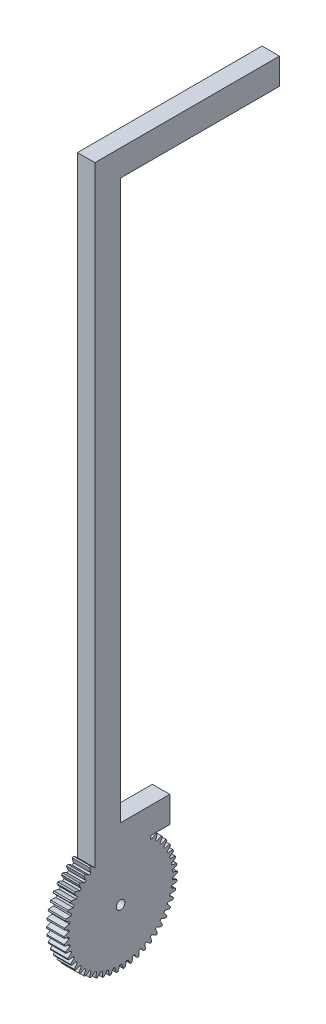
SolidWorks part; units mm, degrees
ref_plane "Plane1" through (0, 0, 0) normal (0, 0, 1) x (1, 0, 0)
ref_plane "Plane2" through (0, 0, 0) normal (0, 1, 0) x (1, 0, 0)
ref_plane "Plane3" through (0, 0, 0) normal (1, 0, 0) x (0, 0, -1)
sketch "HoldingSke" plane through (0, 0, 0) normal (0, 1, 0) x (1, 0, 0)
  line L0 (0, 0) -> (2.5712, -3.0642)
  line L1 (-15, 0) -> (100, 0) construction
  line L2 (0, 0) -> (-2.1039, 2.3779)
  line L3 (0, 0) -> (-11.863, 4.5341)
  line L4 (0, 0) -> (5.5511, 6.6156)
  line L5 (0, 0) -> (-46.8476, -17.4728)
  line L6 (0, 0) -> (-1.6579, -1.1186)
  line L7 (-2.1039, 2.3779) -> (8.6586, 51.2059)
  line L8 (-76.2, 54.61) -> (-76.1, 54.61)
  line L9 (-71.009, 38.7566) -> (-53.1078, 45.2721)
  line L10 (-76.2, 71.12) -> (104.1128, 71.12)
  line L11 (0, 0) -> (-2, 0)
  line L12 (-76.2, 101.6) -> (-76.192, 101.6)
  line L13 (24.9733, 27.94) -> (52.9518, 28.4284)
  line L14 (24.9733, 27.94) -> (24.9743, 27.94)
  line L15 (24.9733, 27.94) -> (100.4006, 29.5858)
  line L16 (-63.627, -0.25) -> (-12.827, -0.25)
  circle A0 centre (0, 0) radius 0.5
  circle A1 centre (0, 0) radius 5.9365
  circle A2 centre (0, 0) radius 37.5
  circle A3 centre (0, 0) radius 0.5
  dimension "MHD" = 11.873
  dimension "Hub_dia" = 75
  dimension "Bore" = 1
  dimension "MBD" = 1
  dimension "Num_teeth" = 50
  dimension "Pitch" = 4
  dimension "Overall_len" = 50
  dimension "Show_teeth" = 50
  dimension "Thickness" = 2
  dimension "OAL" = 50.0001
  dimension "T_dim" = 0.1
  dimension "Ap" = 20
  dimension "H" = 19.05
  dimension "Pitch_radius" = 180.3128
  dimension "Width" = 2
  dimension "Backlash" = 0.008
  dimension "Addendum_fac" = 1
  dimension "Dedendum_fac" = 1.25
  dimension "Clearance_fac" = 0.25
  dimension "Dedendum_add" = 0.001
  dimension "Module" = 0.25
sketch "BasProSke" plane through (0, 0, 0) normal (0, 1, 0) x (1, 0, 0)
  line L0 (-10, 0) -> (60, 0) construction
  line L1 (0, 0) -> (0, 6.5)
  line L2 (0, 0) -> (2, 0)
  line L3 (2, 0) -> (2, 6.5)
  line L4 (2, 6.5) -> (0, 6.5)
  dimension "Thickness" = 2
  dimension "Diameter" = 13
revolve "Base-Revolve" add sketch "BasProSke" angle 360 about L0
sketch "TooCutSke" plane through (0, 0, 0) normal (1, 0, 0) x (0, 0, -1)
  line L1 (0, 0) -> (0, 107) construction
  line L2 (0, 0) -> (-0.2103, 6.2465) construction
  line L3 (0, 0) -> (-0.7845, 12.47) construction
  line L4 (-0.2103, 6.2465) -> (-0.3923, 6.235) construction
  arc A0 (0.1067, 5.9355) -> (-0.1067, 5.9355) centre (0, 0) ccw
  arc A1 (0.3398, 6.5165) -> (-0.3398, 6.5165) centre (0, 0) ccw
  circle A2 centre (0, 0) radius 6.25 construction
  circle A3 centre (0, 0) radius 5.8731 construction
  arc A4 (-0.1067, 5.9355) -> (-0.3398, 6.5165) centre (-2.5252, 5.3025) ccw
  arc A5 (0.3398, 6.5165) -> (0.1067, 5.9355) centre (2.5252, 5.3025) ccw
  dimension "Root_dia" = 11.873
  dimension "Overcut_dia" = 13.0508
  dimension "Pitch_dia" = 12.5
  dimension "Base_dia" = 11.7462
  dimension "Flank_rad" = 2.5
  dimension "Half_ang" = 3.6
  dimension "Half_CT" = 0.1823
extrude "ToothCut" cut sketch "TooCutSke" along normal through all
fillet "Breaks" [suppressed] radius 0.005
fillet "RootFillets" [suppressed] radius 0.0635
pattern_circular "TeethCuts" count 50 every 7.2 about axis through (-10, 0, 0) along (1, 0, 0) of "ToothCut", "RootFillets", "Breaks"
sketch "HubNeaOneSke" plane through (0, 0, 0) normal (-1, 0, 0) x (0, 0, 1)
  circle A0 centre (0, 0) radius 5.9365
  dimension "Diameter" = 11.873
extrude "HubNearOne" [suppressed] add sketch "HubNeaOneSke" along normal blind 48.0001
sketch "HubNeaBotSke" plane through (0, 0, 0) normal (-1, 0, 0) x (0, 0, 1)
  circle A0 centre (0, 0) radius 5.9365
  dimension "Diameter" = 11.873
extrude "HubNearBoth" [suppressed] add sketch "HubNeaBotSke" along normal blind 24
ref_plane "FarPln" through (2, 0, 0) normal (1, 0, 0) x (0, 0, -1)
sketch "HubFarSke" plane through (2, 0, 0) normal (1, 0, 0) x (0, 0, -1)
  circle A0 centre (0, 0) radius 5.9365
  dimension "Diameter" = 11.873
extrude "HubFar" [suppressed] add sketch "HubFarSke" along normal blind 24
sketch "BorSke" plane through (0, 0, 0) normal (1, 0, 0) x (0, 0, -1)
  circle A0 centre (0, 0) radius 0.5
  dimension "Diameter" = 1
extrude "Bore" cut sketch "BorSke" along normal mid plane 100.0001
sketch "KeySke" plane through (0, 0, 0) normal (1, 0, 0) x (0, 0, -1)
  line L0 (-0.05, 0) -> (-0.05, 0.6)
  line L1 (-0.05, 0.6) -> (0.05, 0.6)
  line L2 (0.05, 0.6) -> (0.05, 0)
  line L3 (0, 0) -> (0, 34) construction
  line L4 (-0.05, 0) -> (0.05, 0)
  dimension "Offset" = 0.6
  dimension "Width" = 0.1
extrude "Keyway" [suppressed] cut sketch "KeySke" along normal mid plane 100.0001
pattern_circular "Keyway2" [suppressed] count 2 every 90 about axis through (-10, 0, 0) along (1, 0, 0)
sketch "Sketch1" plane through (2, 0, 0) normal (1, 0, 0) x (0, 0, -1)
  line L0 (0, 0.5) -> (0, 5.9365)
  line L1 (0, 5.9365) -> (0, 11.2268)
  line L3 (-2.953, 5.1499) -> (2.953, 5.1499)
  line L5 (-2.953, 5.1499) -> (3.2527, 5.1499)
  line L9 (3.2527, 5.1499) -> (5.6313, 5.1499)
  line L11 (2.7061, 8.1499) -> (5.6313, 8.1499)
  line L12 (5.6313, 5.1499) -> (5.6313, 8.1499)
  line L13 (11.576, 75.1499) -> (18.2089, 75.1499)
  line L15 (12.7575, 72.1499) -> (18.2089, 72.1499)
  line L16 (18.2089, 75.1499) -> (18.2089, 72.1499)
  line L17 (-2.953, 5.1499) -> (-2.953, 75.1499)
  line L18 (-2.953, 75.1499) -> (11.576, 75.1499)
  line L19 (2.7061, 8.1499) -> (0, 8.1499)
  line L20 (0, 8.1499) -> (0, 72.1499)
  line L21 (12.7575, 72.1499) -> (0, 72.1499)
  circle A0 centre (0, 0) radius 0.5 construction
  arc A1 (0.1067, 5.9355) -> (-0.1067, 5.9355) centre (0, 0) ccw construction
  point P8 (-2.953, 74.6173)
  point P11 (-2.953, 74.5687)
  dimension "D1" = 70
  dimension "D3" = 3
  dimension "D5" = 3
extrude "Boss-Extrude1" add sketch "Sketch1" against normal blind 2 contours L5 L9 L12 L11 L19 L20 L21 L15 L16 L13 L18 L17
equation "' \"Module@HoldingSke\" = 6.35"
equation "' \"Num_teeth@HoldingSke\" = 12"
equation "' \"Ap@HoldingSke\" =  20"
equation "' \"Ap@HoldingSke\" = 20"
equation "' \"Width@HoldingSke\" = 0.5 * 25.4"
equation "' \"Hub_dia@HoldingSke\"= 1 * 25.4"
equation "' \"Hub_dia@HoldingSke\" = 1 * 25.4"
equation "' \"Overall_len@HoldingSke\" = 1.0 * 25.4"
equation "' \"Bore@HoldingSke\" = 0.75 * 25.4"
equation "' \"T_dim@HoldingSke\" = 0.1 * 25.4"
equation "' \"Width@KeySke\" = 0.25 * 25.4"
equation "' \"Show_teeth@HoldingSke\" = 13"
equation "' \"Backlash@HoldingSke\" = 0.009 * 25.4"
equation "' \"Addendum_fac@HoldingSke\" = 1.0"
equation "' \"Dedendum_fac@HoldingSke\" = 1.25"
equation "' \"Dedendum_add@HoldingSke\" = 0.00005 * 25.4"
equation "' \"Clearance_fac@HoldingSke\" = 0.25"
equation "\"Pitch@HoldingSke\" = 1 / \"Module@HoldingSke\""
equation "\"Overcut_dia@TooCutSke\" = (\"Num_teeth@HoldingSke\" + 2 * \"Addendum_fac@HoldingSke\") / \"Pitch@HoldingSke\" + 0.002 * 25.4"
equation "\"Pitch_dia@TooCutSke\" = \"Num_teeth@HoldingSke\" / \"Pitch@HoldingSke\""
equation "\"Base_dia@TooCutSke\" = \"Num_teeth@HoldingSke\" / \"Pitch@HoldingSke\" * cos((\"Ap@HoldingSke\"  * 3.14159265 / 180))"
equation "\"Root_dia@TooCutSke\" = (\"Num_teeth@HoldingSke\" + 2) / \"Pitch@HoldingSke\" - 2 * (\"Addendum_fac@HoldingSke\" + \"Dedendum_fac@HoldingSke\") / \"Pitch@HoldingSke\" - \"Dedendum_add@HoldingSke\" * 2"
equation "\"Half_ang@TooCutSke\" = 180 / \"Num_teeth@HoldingSke\""
equation "\"Half_CT@TooCutSke\" = \"Num_teeth@HoldingSke\" / \"Pitch@HoldingSke\" * sin((3.14159265 / 2 / \"Num_teeth@HoldingSke\")) / 2 - 7 * \"Backlash@HoldingSke\" / 4"
equation "\"Flank_rad@TooCutSke\" = \"Num_teeth@HoldingSke\" / \"Pitch@HoldingSke\" / 5"
equation "\"Radius@RootFillets\" = \"Clearance_fac@HoldingSke\" / \"Pitch@HoldingSke\" + \"Dedendum_add@HoldingSke\""
equation "\"Break_rad@Breaks\" = 0.02 / \"Pitch@HoldingSke\""
equation "\"Thickness@HoldingSke\" = \"Width@HoldingSke\""
equation "\"OAL@HoldingSke\" = \"Thickness@HoldingSke\""
equation "\"MHD@HoldingSke\" = (\"Num_teeth@HoldingSke\" + 2) / \"Pitch@HoldingSke\" - 2 * (\"Addendum_fac@HoldingSke\" + \"Dedendum_fac@HoldingSke\")  / \"Pitch@HoldingSke\" - \"Dedendum_add@HoldingSke\" * 2"
equation "\"MBD@HoldingSke\" = (\"Num_teeth@HoldingSke\" + 2) / \"Pitch@HoldingSke\" - 2 * (\"Addendum_fac@HoldingSke\" + \"Dedendum_fac@HoldingSke\")  / \"Pitch@HoldingSke\" - \"Dedendum_add@HoldingSke\" * 2 - 0.002 * 25.4"
equation "\"MHD@HoldingSke\" = ((sgn( \"MHD@HoldingSke\" - \"Hub_dia@HoldingSke\" )-1)*( \"MHD@HoldingSke\" - \"Hub_dia@HoldingSke\" ))/-2+ \"Hub_dia@HoldingSke\""
equation "\"MBD@HoldingSke\" = ((sgn( \"MBD@HoldingSke\" - \"Bore@HoldingSke\" )-1)*( \"MBD@HoldingSke\" - \"Bore@HoldingSke\" ))/-2+ \"Bore@HoldingSke\""
equation "\"OAL@HoldingSke\" = ((sgn( \"OAL@HoldingSke\" - \"Overall_len@HoldingSke\" )+1)*( \"OAL@HoldingSke\" - \"Overall_len@HoldingSke\" ))/2 + \"Overall_len@HoldingSke\" + 0.000002 * 25.4"
equation "\"Num_teeth@TeethCuts\" = int( \"Show_teeth@HoldingSke\" ) + 1"
equation "\"Num_teeth@TeethCuts\" = ((sgn( \"Num_teeth@TeethCuts\" - \"Num_teeth@HoldingSke\" )-1)*( \"Num_teeth@TeethCuts\" - \"Num_teeth@HoldingSke\" ))/-2+ \"Num_teeth@HoldingSke\""
equation "\"Num_teeth@TeethCuts\" = ((sgn( \"Num_teeth@TeethCuts\" - 2.0)+1)*( \"Num_teeth@TeethCuts\" - 2.0))/2 +2.0"
equation "\"Angle@TeethCuts\" = 360.0 / \"Num_teeth@HoldingSke\""
equation "\"Diameter@BasProSke\" = (\"Num_teeth@HoldingSke\" + 2 * \"Addendum_fac@HoldingSke\") / \"Pitch@HoldingSke\""
equation "\"Thickness@BasProSke\"  = \"Thickness@HoldingSke\""
equation "' \"Fillet_rad@BasProSke\" =  \"Thickness@HoldingSke\" * 0.05"
equation "' \"Fillet_rad@BasProSke\" = \"Thickness@HoldingSke\" * 0.05"
equation "\"MHD@HoldingSke\" = ((sgn( \"MHD@HoldingSke\" - \"Root_dia@TooCutSke\" )-1)*( \"MHD@HoldingSke\" - \"Root_dia@TooCutSke\" ))/-2+ \"Root_dia@TooCutSke\""
equation "\"Diameter@HubNeaOneSke\" = \"MHD@HoldingSke\""
equation "\"Length@HubNearOne\" = \"OAL@HoldingSke\" - \"Thickness@BasProSke\""
equation "\"Diameter@HubNeaBotSke\" = \"MHD@HoldingSke\""
equation "\"Length@HubNearBoth\" = ( \"OAL@HoldingSke\" - \"Thickness@BasProSke\" ) / 2.0"
equation "\"Thickness@FarPln\" = \"Thickness@BasProSke\""
equation "\"Diameter@HubFarSke\" = \"MHD@HoldingSke\""
equation "\"Length@HubFar\" = ( \"OAL@HoldingSke\" - \"Thickness@BasProSke\" ) / 2.0"
equation "\"Diameter@BorSke\" = \"MBD@HoldingSke\""
equation "\"D1@Bore\" = \"OAL@HoldingSke\" * 2.0"
equation "\"D1@Keyway\" = \"OAL@HoldingSke\" * 2.0"
equation "\"Offset@KeySke\" = \"T_dim@HoldingSke\" + \"MBD@HoldingSke\" / 2.0"
